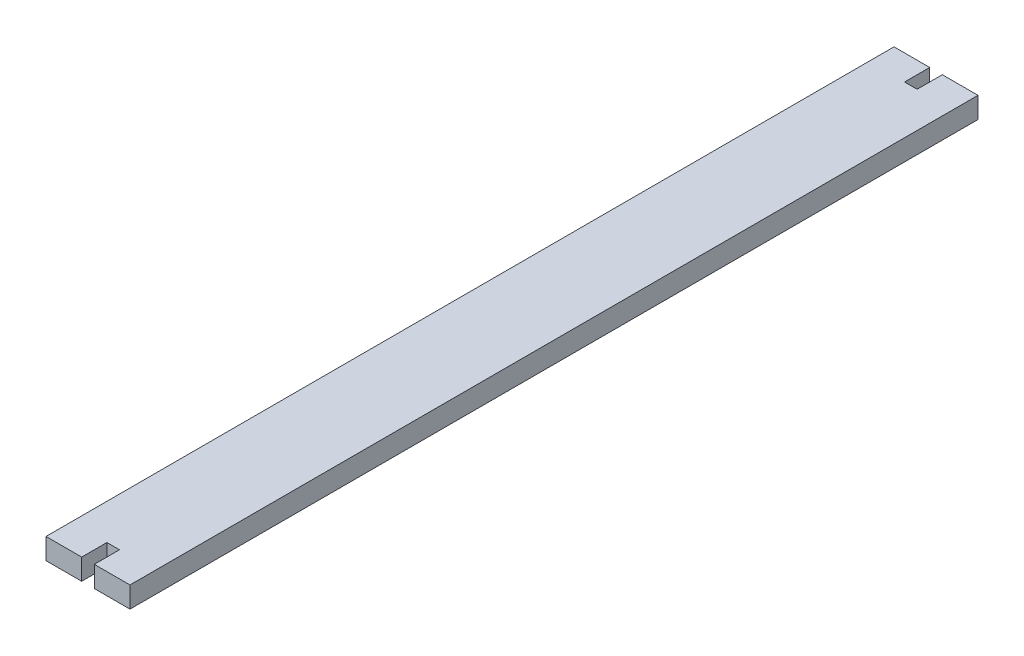
SolidWorks part; units mm, degrees
ref_plane "Front Plane" through (0, 0, 0) normal (0, 0, 1) x (1, 0, 0)
ref_plane "Top Plane" through (0, 0, 0) normal (0, 1, 0) x (1, 0, 0)
ref_plane "Right Plane" through (0, 0, 0) normal (1, 0, 0) x (0, 0, -1)
other "Configuration Table"
sketch "Sketch1" plane through (0, 0, 0) normal (0, 1, 0) x (1, 0, 0)
  line L1 (10, -101) -> (-10, -101)
  line L2 (10, -101) -> (10, 101)
  line L3 (10, 101) -> (-10, 101)
  line L4 (-10, -101) -> (-10, 101)
  line L5 (10, -101) -> (-10, 101) construction
  line L6 (10, 101) -> (-10, -101) construction
  point P0 (0, 0)
  dimension "D1" = 20
  dimension "D2" = 202
extrude "Boss-Extrude1" add sketch "Sketch1" against normal blind 5
sketch "Sketch2" plane through (0, 0, 0) normal (0, 1, 0) x (1, 0, 0)
  line L14 (1.5, -95) -> (-1.5, -95)
  line L22 (0, -101) -> (0, 101) construction
  line L23 (-10, -101) -> (10, -101) construction
  line L24 (10, 101) -> (-10, 101) construction
  line L25 (1.5, -95) -> (1.5, -101)
  line L26 (1.5, 95) -> (-1.5, 95)
  line L27 (1.5, 95) -> (1.5, 101)
  line L28 (1.5, 101) -> (-1.5, 101)
  line L29 (-1.5, 95) -> (-1.5, 101)
  line L30 (1.5, 95) -> (-1.5, 101) construction
  line L31 (1.5, 101) -> (-1.5, 95) construction
  line L32 (1.5, -101) -> (-1.5, -101)
  line L33 (-1.5, -95) -> (-1.5, -101)
  line L34 (1.5, -95) -> (-1.5, -101) construction
  line L35 (1.5, -101) -> (-1.5, -95) construction
  point P6 (0, 98)
  point P11 (0, -98)
  dimension "D1" = 6
  dimension "D2" = 3
  dimension "D3" = 6
extrude "Cut-Extrude1" cut sketch "Sketch2" against normal through all
